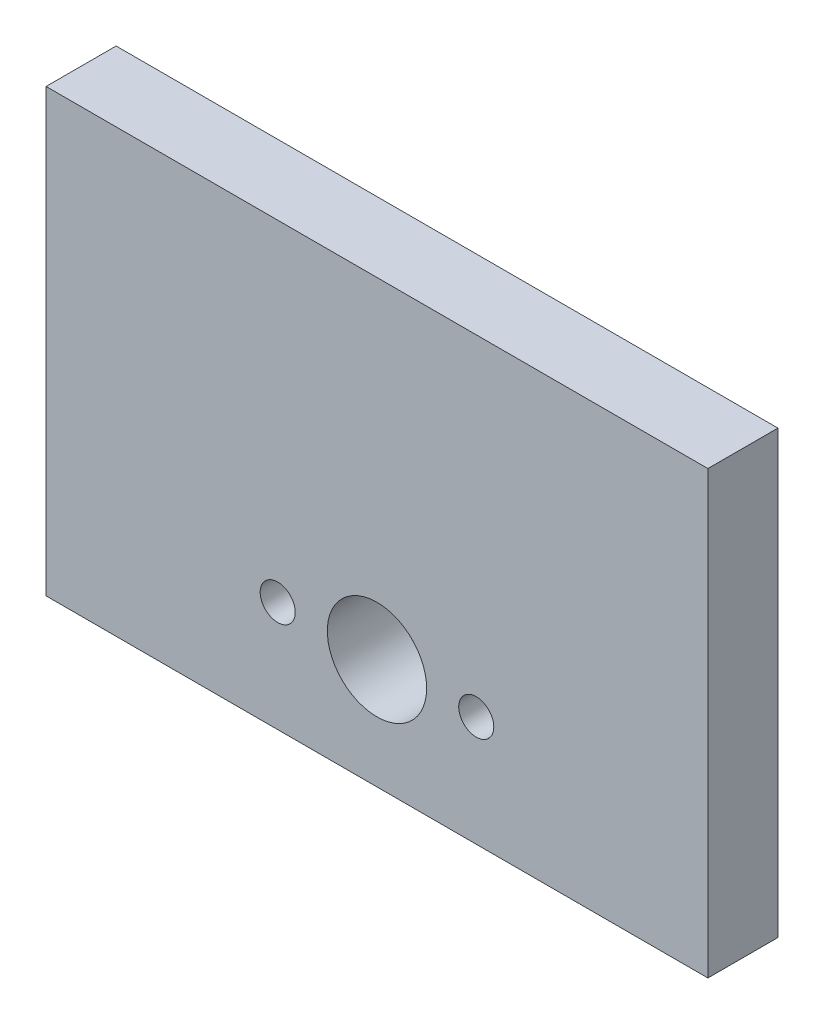
SolidWorks part; units mm, degrees
ref_plane "Front Plane" through (0, 0, 0) normal (0, 0, 1) x (1, 0, 0)
ref_plane "Top Plane" through (0, 0, 0) normal (0, 1, 0) x (1, 0, 0)
ref_plane "Right Plane" through (0, 0, 0) normal (1, 0, 0) x (0, 0, -1)
sketch "Sketch1" plane through (0, 0, 0) normal (0, 0, 1) x (1, 0, 0)
  line L6 (30, -18) -> (30, -30) construction
  line L9 (17.5, -22.5) -> (42.5, -22.5)
  line L16 (0, 0) -> (60, 0)
  line L21 (0, 0) -> (0, -40)
  line L22 (0, -40) -> (60, -40)
  line L23 (60, 0) -> (60, -40)
  line L24 (17.5, -22.5) -> (17.5, -37.5)
  line L25 (15, -18) -> (45, -18) construction
  line L26 (15, -18) -> (15, -38) construction
  line L27 (15, -38) -> (45, -38) construction
  line L28 (45, -18) -> (45, -38) construction
  line L29 (17.5, -37.5) -> (42.5, -37.5)
  line L30 (15, -30) -> (45, -30) construction
  line L31 (42.5, -22.5) -> (42.5, -37.5)
  circle A1 centre (30, -30) radius 4.5
  circle A2 centre (30, -30) radius 4.5
  circle A3 centre (21, -30) radius 1.59
  circle A4 centre (39, -30) radius 1.59
  circle A5 centre (21, -30) radius 2.3241 construction
  point P19 (30, -18)
  point P21 (30, -22.5)
  point P23 (42.5, -30)
  point P28 (29.1383, -30)
  dimension "D1" = 9
  dimension "D2" = 9
  dimension "D3" = 25
  dimension "D11" = 2
  dimension "D13" = 4.6482
  dimension "D4" = 3.18
  dimension "D8" = 60
  dimension "D6" = 3.5
  dimension "D7" = 40
  dimension "D9" = 30
  dimension "D10" = 20
  dimension "D12" = 15
  dimension "D5" = 18
extrude "Boss-Extrude1" add sketch "Sketch1" along normal blind 6.35 contours L23 L16 L21 L22 L9 L31 L29 L24 | L31 L9 L24 L29 A4 A3 A1
